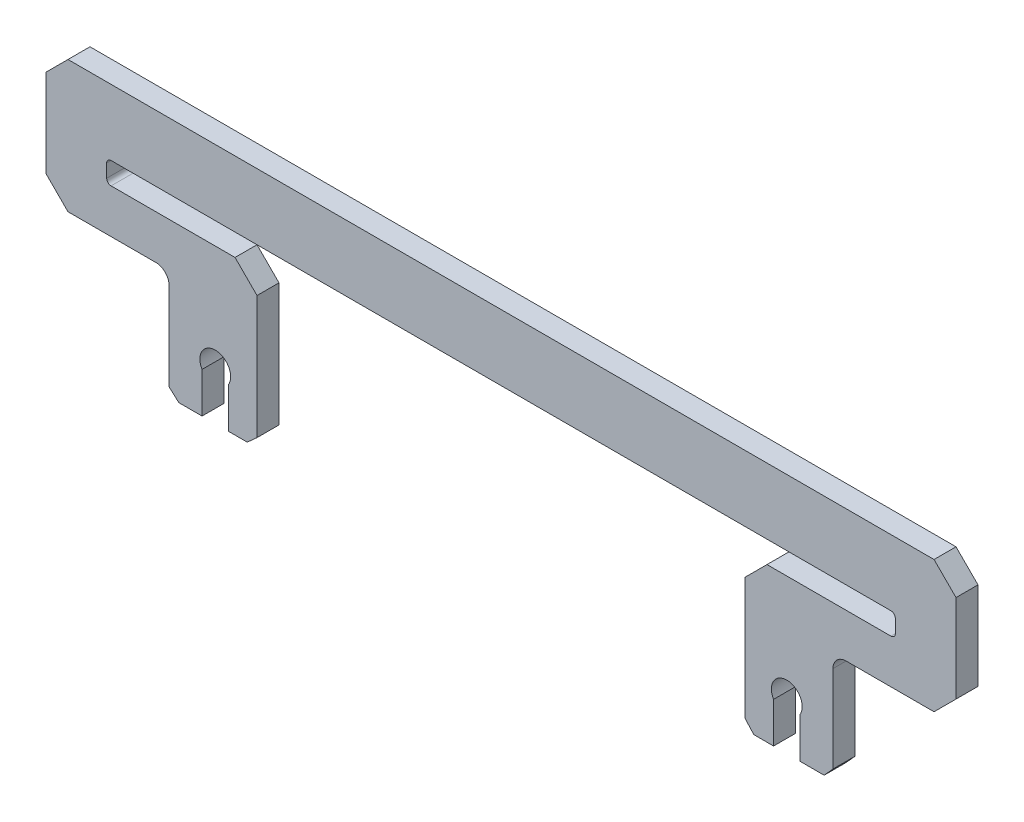
SolidWorks part; units mm, degrees
ref_plane "정면" through (0, 0, 0) normal (0, 0, 1) x (1, 0, 0)
ref_plane "윗면" through (0, 0, 0) normal (0, 1, 0) x (1, 0, 0)
ref_plane "우측면" through (0, 0, 0) normal (1, 0, 0) x (0, 0, -1)
sketch "스케치1" plane through (0, 0, 0) normal (0, 0, 1) x (1, 0, 0)
  line L1 (-88.5, -7.5) -> (88.5, -7.5)
  line L2 (-88.5, -7.5) -> (-88.5, 7.5)
  line L3 (-88.5, 7.5) -> (88.5, 7.5)
  line L4 (88.5, -7.5) -> (88.5, 7.5)
  line L5 (-88.5, -7.5) -> (88.5, 7.5) construction
  line L6 (-88.5, 7.5) -> (88.5, -7.5) construction
  point P0 (0, 0)
  dimension "D1" = 177
  dimension "D2" = 15
extrude "보스-돌출1" add sketch "스케치1" along normal blind 5
sketch "스케치3" plane through (0, 0, 5) normal (0, 0, 1) x (1, 0, 0)
  line L0 (-88.5, 7.5) -> (-88.5, -7.5) construction
  line L1 (88.5, 7.5) -> (103.5, 7.5)
  line L2 (88.5, 7.5) -> (88.5, -47.5)
  line L3 (88.5, -47.5) -> (103.5, -47.5)
  line L4 (103.5, 7.5) -> (103.5, -47.5)
  line L5 (-88.5, 7.5) -> (-103.5, 7.5)
  line L6 (-88.5, 7.5) -> (-88.5, -47.5)
  line L7 (-88.5, -47.5) -> (-103.5, -47.5)
  line L8 (-103.5, 7.5) -> (-103.5, -47.5)
  dimension "D1" = 15
  dimension "D2" = 55
extrude "보스-돌출3" add sketch "스케치3" against normal blind 5
sketch "스케치9" plane through (0, 0, 5) normal (0, 0, 1) x (1, 0, 0)
  line L0 (-88.5, -47.5) -> (-88.5, -7.5) construction
  line L1 (-88.5, -12.5) -> (-55.5, -12.5)
  line L2 (-88.5, -12.5) -> (-88.5, -47.5)
  line L3 (-88.5, -47.5) -> (-55.5, -47.5)
  line L4 (-55.5, -12.5) -> (-55.5, -47.5)
  line L5 (88.5, -7.5) -> (88.5, -47.5) construction
  line L6 (88.5, -12.5) -> (55.5, -12.5)
  line L7 (88.5, -12.5) -> (88.5, -47.5)
  line L8 (88.5, -47.5) -> (55.5, -47.5)
  line L9 (55.5, -12.5) -> (55.5, -47.5)
  line L10 (-103.5, -47.5) -> (-88.5, -47.5) construction
  dimension "D1" = 33
  dimension "D2" = 35
extrude "보스-돌출5" add sketch "스케치9" against normal blind 5
sketch "스케치8" plane through (0, 0, 5) normal (0, 0, 1) x (1, 0, 0)
  line L5 (-88.5, -7.5) -> (-88.7, -7.5)
  line L6 (-88.5, -7.5) -> (-88.5, -12.5)
  line L7 (-88.5, -12.5) -> (-88.7, -12.5)
  line L8 (-89.7, -8.5) -> (-89.7, -11.5)
  line L9 (88.5, -7.5) -> (88.7, -7.5)
  line L10 (88.5, -7.5) -> (88.5, -12.5)
  line L11 (88.5, -12.5) -> (88.7, -12.5)
  line L12 (89.7, -8.5) -> (89.7, -11.5)
  arc A0 (88.7, -12.5) -> (89.7, -11.5) centre (88.7, -11.5) ccw
  arc A1 (88.7, -7.5) -> (89.7, -8.5) centre (88.7, -8.5) cw
  arc A2 (-88.7, -12.5) -> (-89.7, -11.5) centre (-88.7, -11.5) cw
  arc A3 (-88.7, -7.5) -> (-89.7, -8.5) centre (-88.7, -8.5) ccw
  point P15 (89.7, -7.5)
  point P23 (-89.7, -7.5)
  dimension "D1" = 1.2
  dimension "D3" = 1
  dimension "D2" = 1.2
extrude "컷-돌출4" cut sketch "스케치8" against normal up to next
sketch "스케치10" plane through (0, 0, 5) normal (0, 0, 1) x (1, 0, 0)
  line L0 (0, 7.5) -> (0, -36.5) construction
  line L1 (103.5, 7.5) -> (-103.5, 7.5) construction
  line L2 (0, -36.5) -> (-65, -36.5) construction
  line L3 (-88.7, -7.5) -> (88.7, -7.5) construction
  line L4 (-103.5, 7.5) -> (-103.5, -47.5) construction
  line L6 (0, -36.5) -> (65, -36.5) construction
  circle A0 centre (65, -36.5) radius 3
  circle A1 centre (-65, -36.5) radius 3
  dimension "D3" = 6
  dimension "D1" = 38.5
  dimension "D2" = 29
extrude "컷-돌출5" cut sketch "스케치10" against normal up to next
sketch "스케치13" plane through (0, 0, 0) normal (0, 0, -1) x (-1, 0, 0)
  line L0 (-103.5, -47.5) -> (-103.5, 7.5) construction
  line L1 (-103.5, -47.5) -> (-75.5, -47.5)
  line L2 (-103.5, -47.5) -> (-103.5, -22.5)
  line L3 (-103.5, -22.5) -> (-75.5, -22.5)
  line L4 (-75.5, -47.5) -> (-75.5, -22.5)
  line L5 (-88.7, -12.5) -> (-55.5, -12.5) construction
  line L6 (103.5, -47.5) -> (75.5, -47.5)
  line L7 (103.5, -47.5) -> (103.5, -22.5)
  line L8 (103.5, -22.5) -> (75.5, -22.5)
  line L9 (75.5, -47.5) -> (75.5, -22.5)
  line L10 (-55.5, -12.5) -> (-55.5, -47.5) construction
  dimension "D1" = 10
  dimension "D2" = 20
extrude "컷-돌출8" cut sketch "스케치13" against normal blind 10
chamfer "모따기4" distance 5 angle 45 6 edges at (-103.5, 7.5, 2.5) (-103.5, -22.5, 2.5) (-55.5, -12.5, 2.5) (55.5, -12.5, 2.5) (103.5, -22.5, 2.5) (103.5, 7.5, 2.5)
fillet "필렛3" radius 3 2 edges at (-75.5, -22.5, 2.5) (75.5, -22.5, 2.5)
sketch "스케치14" plane through (0, 0, 0) normal (0, 0, -1) x (-1, 0, 0)
  line L0 (-55.5, -47.5) -> (-75.5, -47.5) construction
  line L1 (-68, -36.5) -> (-62, -36.5)
  line L2 (-68, -36.5) -> (-68, -47.5)
  line L3 (-68, -47.5) -> (-62, -47.5)
  line L4 (-62, -36.5) -> (-62, -47.5)
  line L5 (75.5, -47.5) -> (55.5, -47.5) construction
  line L6 (62, -36.5) -> (68, -36.5)
  line L7 (62, -36.5) -> (62, -47.5)
  line L8 (62, -47.5) -> (68, -47.5)
  line L9 (68, -36.5) -> (68, -47.5)
  circle A0 centre (-65, -36.5) radius 3 construction
  circle A1 centre (65, -36.5) radius 3 construction
extrude "컷-돌출9" cut sketch "스케치14" against normal blind 10
sketch "스케치15" plane through (0, 0, 0) normal (0, 0, -1) x (-1, 0, 0)
  line L0 (0, -7.5) -> (0, -47.8058) construction
  line L1 (88.7, -7.5) -> (-88.7, -7.5) construction
  circle A0 centre (65, -36.5) radius 3.5
  circle A1 centre (-65, -36.5) radius 3.5
  dimension "D1" = 7
extrude "컷-돌출10" cut sketch "스케치15" against normal blind 10
chamfer "모따기5" distance 2 angle 48 4 edges at (-55.5, -47.5, 2.5) (55.5, -47.5, 2.5) (-75.5, -47.5, 2.5) (75.5, -47.5, 2.5)
sketch "스케치18" plane through (0, 0, 0) normal (0, 0, -1) x (-1, 0, 0)
  line L0 (-75.5, -45.2788) -> (-75.5, -25.5) construction
  line L2 (-71.5, -35) -> (-75.5, -35)
  line L3 (-71.5, -35) -> (-71.5, -32)
  line L4 (-71.5, -32) -> (-75.5, -32)
  line L5 (-75.5, -35) -> (-75.5, -32)
  line L6 (-55.5, -17.5) -> (-55.5, -45.2788) construction
  line L7 (-58.5, -35) -> (-55.5, -35)
  line L8 (-58.5, -35) -> (-58.5, -32)
  line L9 (-58.5, -32) -> (-55.5, -32)
  line L11 (-55.5, -35) -> (-55.5, -32)
  line L12 (0, 0) -> (0, -52.1121) construction
  line L13 (-58.5, -38) -> (-55.5, -38)
  line L14 (-58.5, -38) -> (-58.5, -41)
  line L15 (-58.5, -41) -> (-55.5, -41)
  line L16 (-55.5, -38) -> (-55.5, -41)
  line L17 (-71.5, -38) -> (-75.5, -38)
  line L18 (-71.5, -38) -> (-71.5, -41)
  line L19 (-71.5, -41) -> (-75.5, -41)
  line L20 (-75.5, -38) -> (-75.5, -41)
  line L21 (75.5, -38) -> (75.5, -41)
  line L22 (71.5, -41) -> (75.5, -41)
  line L23 (71.5, -38) -> (71.5, -41)
  line L24 (71.5, -38) -> (75.5, -38)
  line L25 (55.5, -38) -> (55.5, -41)
  line L26 (58.5, -41) -> (55.5, -41)
  line L27 (58.5, -38) -> (58.5, -41)
  line L28 (58.5, -38) -> (55.5, -38)
  line L29 (55.5, -35) -> (55.5, -32)
  line L30 (58.5, -32) -> (55.5, -32)
  line L31 (58.5, -35) -> (58.5, -32)
  line L32 (58.5, -35) -> (55.5, -35)
  line L33 (75.5, -35) -> (75.5, -32)
  line L34 (71.5, -32) -> (75.5, -32)
  line L35 (71.5, -35) -> (71.5, -32)
  line L36 (71.5, -35) -> (75.5, -35)
  dimension "D1" = 3
extrude "컷-돌출11" [suppressed] cut sketch "스케치18" against normal blind 10
